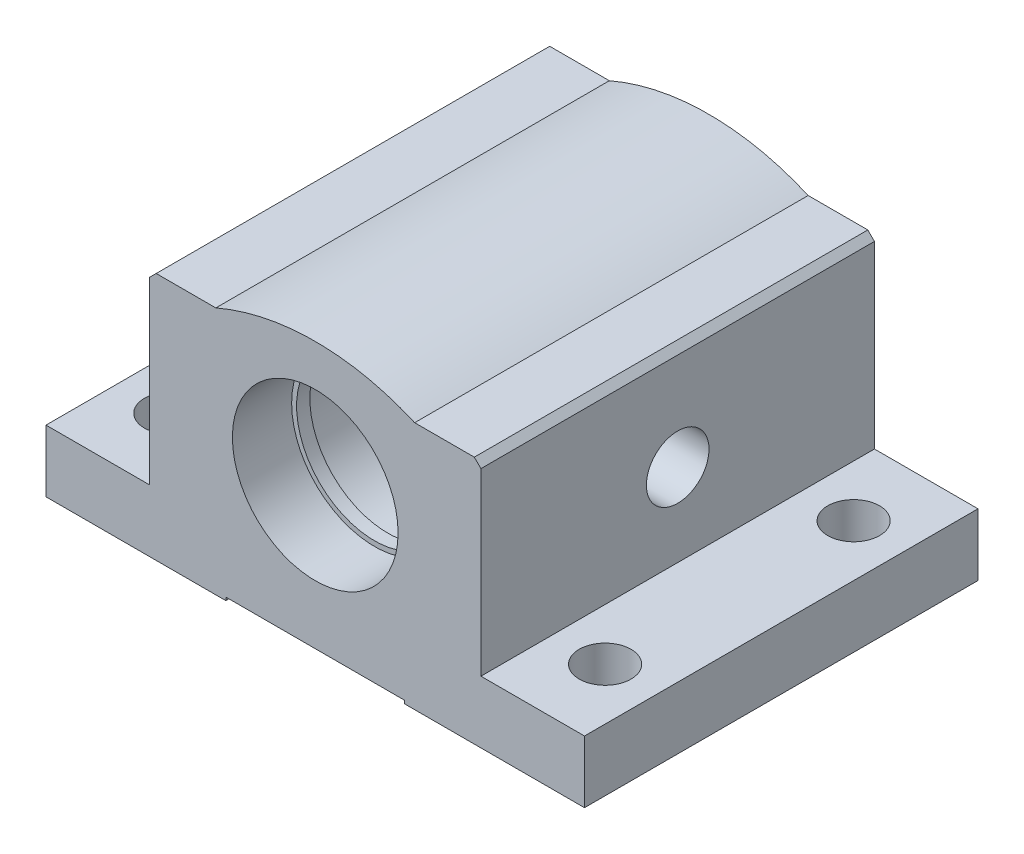
SolidWorks part; units mm, degrees
ref_plane "Front Plane" through (0, 0, 0) normal (0, 0, 1) x (1, 0, 0)
ref_plane "Top Plane" through (0, 0, 0) normal (0, 1, 0) x (1, 0, 0)
ref_plane "Right Plane" through (0, 0, 0) normal (1, 0, 0) x (0, 0, -1)
sketch "Sketch1" plane through (0, 0, 0) normal (0, 0, 1) x (1, 0, 0)
  line L0 (-20.6375, -5.5563) -> (-12.7, -5.5562)
  line L1 (-20.6375, 10.3187) -> (20.6375, 10.3187)
  line L2 (-20.6375, 10.3187) -> (-20.6375, -10.3188)
  line L3 (-20.6375, -10.3188) -> (20.6375, -10.3187)
  line L4 (20.6375, 10.3187) -> (20.6375, -10.3187)
  line L5 (-12.7, -5.5562) -> (-12.7, 8.7312)
  line L6 (-12.7, 8.7312) -> (12.7, 8.7312)
  line L7 (12.7, 8.7312) -> (12.7, -5.5563)
  line L8 (12.7, -5.5563) -> (20.6375, -5.5563)
  line L9 (0, 0.781) -> (0, -10.3188) construction
  circle A0 centre (0, 0.781) radius 6.35
  point P4 (20.6375, 0)
  point P5 (0, 10.3188)
  dimension "ID | For Bearing OD" = 12.7
  dimension "Overall Height" = 20.6375
  dimension "Overall Width" = 41.275
  dimension "Base Thickness" = 4.7625
  dimension "K" = 19.05
  dimension "G" = 25.4
  dimension "Center Height" = 11.0998
sketch "Sketch2" plane through (0, 0, 0) normal (1, 0, 0) x (0, 0, -1)
  line L0 (-15.0812, 0) -> (15.0812, 0) construction
  line L2 (0, 10.3187) -> (0, -10.3187) construction
  line L3 (0, 10.3187) -> (0, -10.3187) construction
  circle A0 centre (0, 0.781) radius 2.4003
  point P2 (0, 0)
  point P11 (-9.525, 0)
  dimension "Grease Hole Diameter" = 4.8006
  dimension "Overall Length" = 30.1625
  dimension "For Maximum Bearing Length" = 19.05
sketch "Sketch3" plane through (0, 0, 0) normal (0, 1, 0) x (1, 0, 0)
  line L1 (-20.6375, 15.0812) -> (20.6375, 15.0812)
  line L2 (-20.6375, 15.0812) -> (-20.6375, -15.0813)
  line L3 (-20.6375, -15.0813) -> (20.6375, -15.0812)
  line L4 (20.6375, 15.0812) -> (20.6375, -15.0812)
  line L5 (-16.6624, 9.525) -> (16.6624, 9.525) construction
  line L6 (-16.6624, 9.525) -> (-16.6624, -9.525) construction
  line L7 (-16.6624, -9.525) -> (16.6624, -9.525) construction
  line L8 (16.6624, 9.525) -> (16.6624, -9.525) construction
  circle A0 centre (-16.6624, 9.525) radius 1.9844
  point P4 (0, 15.0812)
  point P5 (20.6375, 0)
  point P12 (0, 9.525)
  point P13 (16.6624, 0)
  dimension "Mounting Hole Diameter" = 3.9688
  dimension "Mounting Hole Center to Center, Length" = 19.05
  dimension "Mounting Hole Center to Center, Width" = 33.3248
sketch "Sketch4" plane through (0, 0, 0) normal (0, 0, 1) x (1, 0, 0)
  line L0 (-20.6375, -5.5563) -> (-12.7, -5.5562) construction
  line L1 (-20.6375, -5.5563) -> (-12.7, -5.5562)
  line L2 (-20.6375, -10.3188) -> (20.6375, -10.3187) construction
  line L3 (12.7, -5.5563) -> (20.6375, -5.5563) construction
  line L4 (12.7, 8.7312) -> (12.7, -5.5563) construction
  line L5 (-12.7, 8.7312) -> (12.7, 8.7312) construction
  line L6 (-12.7, -5.5562) -> (-12.7, 8.7312) construction
  line L7 (-20.6375, -10.3188) -> (-6.858, -10.3188)
  line L8 (12.7, -5.5563) -> (20.6375, -5.5563)
  line L9 (12.7, 8.7312) -> (12.7, -5.5563)
  line L10 (-12.7, 8.7312) -> (-7.62, 8.7312)
  line L11 (-12.7, -5.5562) -> (-12.7, 8.7312)
  line L12 (-20.6375, -5.5563) -> (-20.6375, -10.3188)
  line L13 (20.6375, -5.5563) -> (20.6375, -10.3187)
  line L14 (7.62, 8.7313) -> (12.7, 8.7312)
  line L15 (-20.6375, 10.3187) -> (20.6375, 10.3187) construction
  line L16 (-6.858, -10.3188) -> (-6.858, -10.0806)
  line L17 (-6.858, -10.0806) -> (6.858, -10.0806)
  line L18 (6.858, -10.0806) -> (6.858, -10.3188)
  line L19 (0, 0.781) -> (0, -10.3188) construction
  line L22 (6.858, -10.3188) -> (20.6375, -10.3187)
  circle A0 centre (0, 0.781) radius 6.35 construction
  circle A1 centre (0, 0.781) radius 6.35
  arc A2 (-7.62, 8.7312) -> (7.62, 8.7313) centre (0, -8.763) cw
  point P14 (0, 10.3187)
  point P17 (0, 10.3187)
  point P20 (0, -10.0806)
  dimension "D1" = 15.24
  dimension "D2" = 13.716
  dimension "D3" = 0.2381
extrude "Boss-Extrude1" add sketch "Sketch4" along normal up to vertex (15.0813 mm away) from vertex at -15.0813 starting at point (0, 0, -15.0812)
sketch "Sketch5" plane through (0, -5.5562, 0) normal (0, 1, 0) x (1, 0, 0)
  circle A0 centre (-16.6624, 9.525) radius 1.9844 construction
  circle A1 centre (-16.6624, 9.525) radius 1.9844
  circle A2 centre (16.6624, 9.525) radius 1.9844
  circle A3 centre (16.6624, -9.525) radius 1.9844
  circle A4 centre (-16.6624, -9.525) radius 1.9844
extrude "Cut-Extrude1" cut sketch "Sketch5" against normal through all
chamfer "Chamfer1" distance 0.508 angle 45 2 edges at (-12.7, 8.7312, 0) (12.7, 8.7312, 0)
ref_plane "Plane1" through (0, 0, 9.525) normal (0, 0, 1) x (1, 0, 0)
sketch "Sketch6" plane through (0, 0, 9.525) normal (0, 0, 1) x (1, 0, 0)
  circle A0 centre (0, 0.781) radius 6.731
  dimension "Retaining Ring Slot OD" = 13.462
extrude "Cut-Extrude2" cut sketch "Sketch6" along normal blind 1.016
mirror "Mirror1" about plane through (0, 0, 0) normal (0, 0, 1) of "Cut-Extrude2"
sketch "Sketch7" plane through (12.7, 0, 0) normal (1, 0, 0) x (0, 0, -1)
  circle A0 centre (0, 0.781) radius 2.4003 construction
  circle A1 centre (0, 0.781) radius 2.4003
extrude "Cut-Extrude3" cut sketch "Sketch7" against normal up to next
sketch "Sketch8" plane through (0, 0, 9.525) normal (0, 0, 1) x (1, 0, 0)
  line L0 (0, 0.781) -> (-3.9513, 4.7324) construction
  line L1 (3.9513, 4.7324) -> (4.7595, 5.5406) construction
  line L2 (0, 0.781) -> (0, 10.3187) construction
  line L3 (0, -5.95) -> (0, -5.569) construction
  line L4 (0, -5.569) -> (0, -5.188) construction
  line L5 (-2.4984, 5.6157) -> (-2.9421, 6.835)
  line L6 (-3.9636, 5.013) -> (-3.6886, 4.7823)
  line L7 (-3.2051, 5.3585) -> (-2.7737, 4.7423) construction
  line L8 (0, -5.188) -> (0, -4.807) construction
  line L9 (-2.7737, 4.7423) -> (0, 0.781) construction
  line L10 (-4.2207, 5.0018) -> (-4.7595, 5.5406) construction
  line L11 (-4.2207, 5.0018) -> (-4.086, 4.8671) construction
  line L12 (-4.086, 4.8671) -> (-3.9513, 4.7324) construction
  line L13 (3.9636, 5.013) -> (3.6886, 4.7823)
  line L14 (2.4984, 5.6157) -> (2.9421, 6.835)
  circle A0 centre (0, 0.781) radius 6.731 construction
  arc A1 (-4.7595, 5.5406) -> (4.7595, 5.5406) centre (0, 0.781) ccw
  arc A2 (-4.2207, 5.0018) -> (4.2207, 5.0018) centre (0, 0.781) ccw
  circle A3 centre (0, 0.781) radius 6.35 construction
  arc A4 (7.62, 8.7313) -> (-7.62, 8.7312) centre (0, -8.763) ccw construction
  arc A6 (-4.2207, 5.0018) -> (-3.9636, 5.013) centre (-4.086, 4.8671) cw
  arc A9 (-4.7595, 5.5406) -> (-2.9421, 6.835) centre (0, 0.781) cw
  arc A10 (-3.6886, 4.7823) -> (-2.4984, 5.6157) centre (-3.2051, 5.3585) ccw
  circle A11 centre (0, 0.781) radius 5.588 construction
  circle A12 centre (-3.2051, 5.3585) radius 0.3761
  arc A13 (4.2207, 5.0018) -> (3.9636, 5.013) centre (4.086, 4.8671) ccw
  circle A14 centre (3.2051, 5.3585) radius 0.3761
  arc A15 (3.6886, 4.7823) -> (2.4984, 5.6157) centre (3.2051, 5.3585) cw
  arc A16 (4.7595, 5.5406) -> (2.9421, 6.835) centre (0, 0.781) ccw
  point P20 (-2.9894, 5.0504)
  dimension "D3" = 30
  dimension "D4" = 10
  dimension "D1" = 45
extrude "Boss-Extrude2" add sketch "Sketch8" along normal blind 1.016 separate body
mirror "Mirror2" about plane through (0, 0, 0) normal (0, 0, 1) of bodies 109
equation "\"D1@Sketch4\"=0.6*\"G@Sketch1\""
equation "\"D2@Sketch4\"=\"D1@Sketch4\"*.9"
equation "\"D1@Chamfer1\"=.02*\"G@Sketch1\""
equation "\"D3@Sketch4\"=.05*\"Base Thickness@Sketch1\""
equation "\"D1@Boss-Extrude2\"=\"Retaining Ring Slot Thickness@Cut-Extrude2\""
